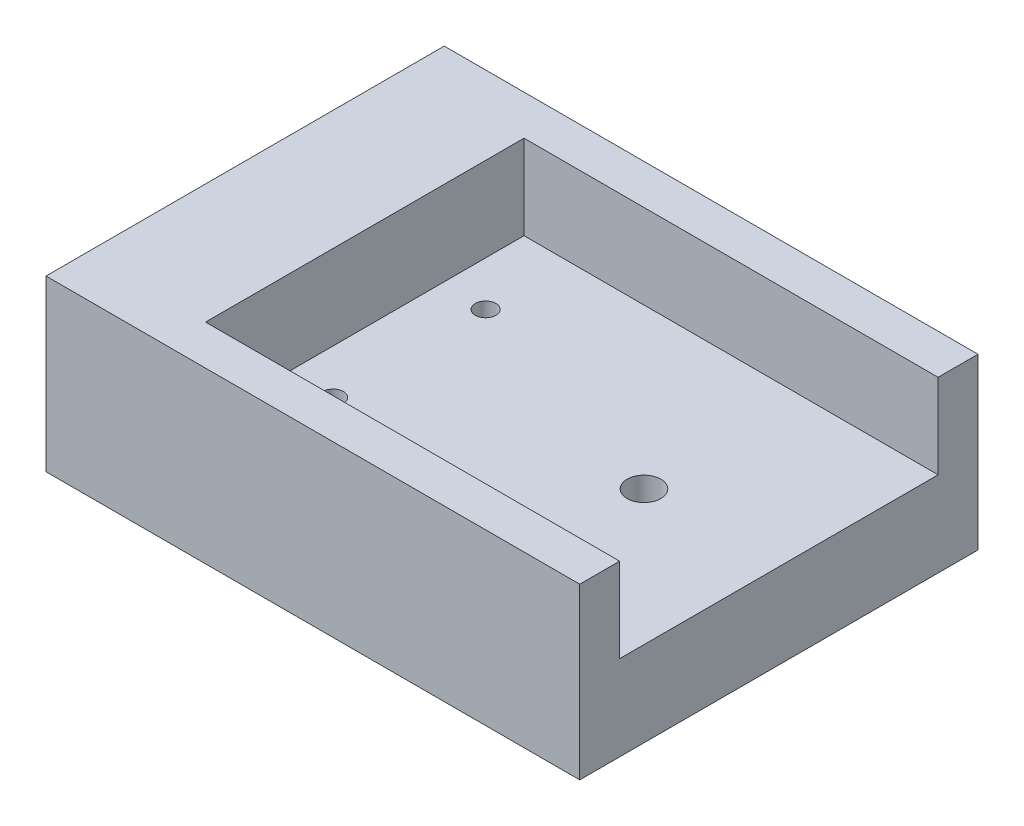
SolidWorks part; units mm, degrees
ref_plane "Front Plane" through (0, 0, 0) normal (0, 0, 1) x (1, 0, 0)
ref_plane "Top Plane" through (0, 0, 0) normal (0, 1, 0) x (1, 0, 0)
ref_plane "Right Plane" through (0, 0, 0) normal (1, 0, 0) x (0, 0, -1)
sketch "Sketch1" plane through (0, 0, 0) normal (0, 1, 0) x (1, 0, 0)
  line L1 (-45.5, 33.95) -> (45.5, 33.95)
  line L2 (-45.5, 33.95) -> (-45.5, -33.95)
  line L3 (-45.5, -33.95) -> (45.5, -33.95)
  line L4 (45.5, 33.95) -> (45.5, -33.95)
  line L5 (-45.5, 33.95) -> (45.5, -33.95) construction
  line L6 (-45.5, -33.95) -> (45.5, 33.95) construction
  point P0 (0, 0)
  dimension "D1" = 67.9
  dimension "D2" = 91
extrude "Boss-Extrude1" add sketch "Sketch1" along normal blind 28.9
sketch "Sketch2" plane through (0, 28.9, 0) normal (0, 1, 0) x (1, 0, 0)
  line L1 (-25.1, 27.15) -> (45.5, 27.15)
  line L2 (-25.1, 27.15) -> (-25.1, -27.15)
  line L3 (-25.1, -27.15) -> (45.5, -27.15)
  line L4 (45.5, 27.15) -> (45.5, -27.15)
  line L5 (-25.1, 27.15) -> (45.5, -27.15) construction
  line L6 (-25.1, -27.15) -> (45.5, 27.15) construction
  line L7 (-45.5, 33.95) -> (-45.5, -33.95) construction
  line L8 (45.5, -33.95) -> (45.5, 33.95) construction
  point P0 (10.2, 0)
  dimension "D1" = 20.4
  dimension "D2" = 54.3
extrude "Cut-Extrude1" cut sketch "Sketch2" against normal offset from surface (14.4 mm away) 14.5 up to face at (0, 0, 0)
sketch "Sketch3" plane through (-45.5, 0, 0) normal (-1, 0, 0) x (0, 0, 1)
  circle A0 centre (0, 5.7504) radius 3.75
  dimension "D1" = 7.5
extrude "Cut-Extrude2" cut sketch "Sketch3" against normal blind 5
sketch "Sketch4" plane through (0, 14.5, 0) normal (0, 1, 0) x (1, 0, 0)
  line L0 (-17.5, 13) -> (-17.5, 3.4074) construction
  line L1 (-19.0849, 0) -> (40.2754, 0) construction
  line L2 (45.5, 27.15) -> (45.5, -27.15) construction
  circle A0 centre (22.5, 0) radius 2.8715
  circle A1 centre (-17.5, 13) radius 1.7547
  circle A2 centre (-17.5, -13) radius 1.7547
  dimension "D1" = 13
  dimension "D2" = 40
  dimension "D3" = 23
extrude "Cut-Extrude3" cut sketch "Sketch4" against normal up to surface (14.5 mm away) up to face at (0, 0, 0)
